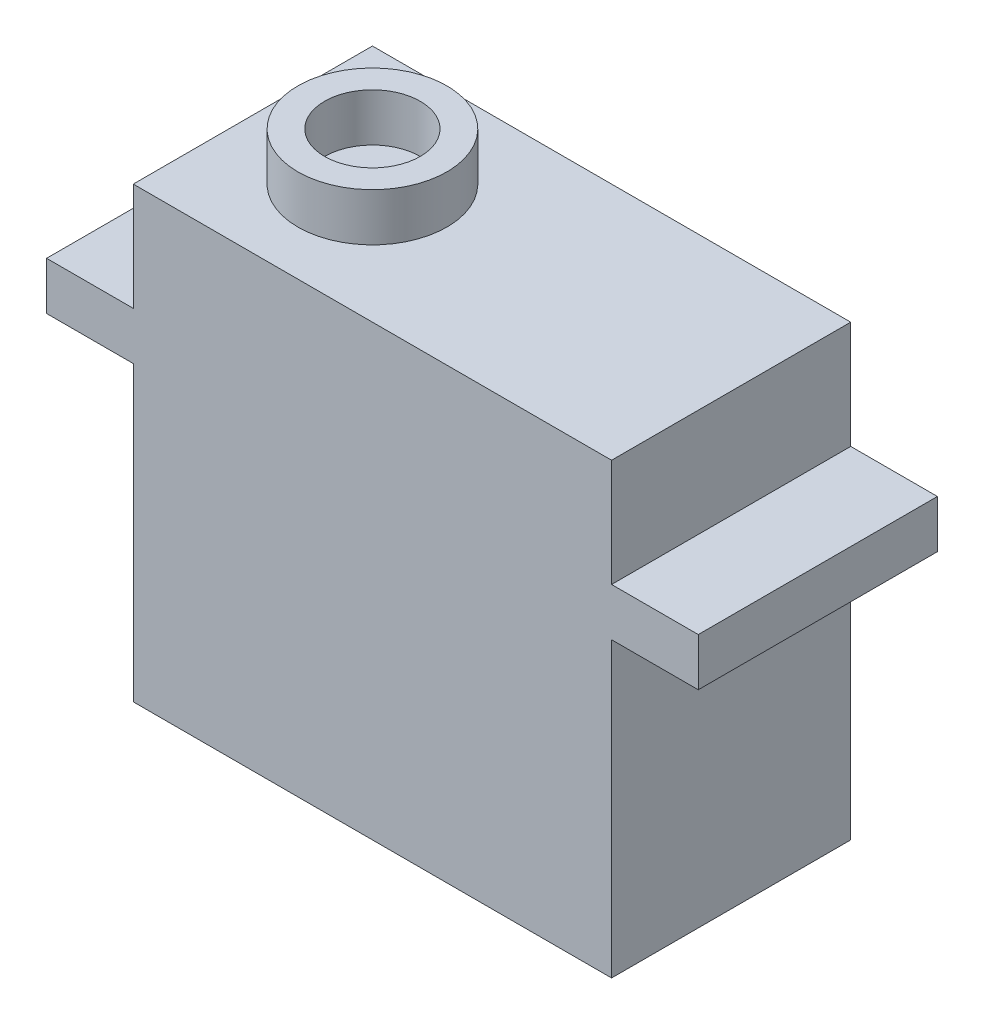
SolidWorks part; units mm, degrees
other "Markup2"
sketch "Sketch6"
other "DetailItem1"
ref_plane "Front Plane" through (0, 0, 0) normal (0, 0, 1) x (1, 0, 0)
ref_plane "Top Plane" through (0, 0, 0) normal (0, 1, 0) x (1, 0, 0)
ref_plane "Right Plane" through (0, 0, 0) normal (1, 0, 0) x (0, 0, -1)
sketch "Sketch1" plane through (0, 0, 0) normal (0, 1, 0) x (1, 0, 0)
  line L1 (0, 0) -> (40, 0)
  line L2 (0, 0) -> (0, 20)
  line L3 (0, 20) -> (40, 20)
  line L4 (40, 0) -> (40, 20)
  dimension "D1" = 20
  dimension "D2" = 40
extrude "Boss-Extrude1" add sketch "Sketch1" along normal blind 24.5
sketch "Sketch2" plane through (0, 24.5, 0) normal (0, 1, 0) x (1, 0, 0)
  line L0 (0, 20) -> (0, 0) construction
  line L5 (47.25, 20) -> (-7.25, 20)
  line L6 (47.25, 20) -> (47.25, 0)
  line L7 (47.25, 0) -> (-7.25, 0)
  line L8 (-7.25, 20) -> (-7.25, 0)
  line L9 (40, 0) -> (40, 20) construction
  dimension "D1" = 7.25
  dimension "D2" = 7.25
  dimension "D3" = 20
extrude "Boss-Extrude2" add sketch "Sketch2" along normal blind 4
sketch "Sketch3" plane through (0, 0, 0) normal (0, 0, 1) x (1, 0, 0)
  line L1 (0, 0) -> (40, 0)
  line L2 (0, 0) -> (0, 37.5)
  line L3 (0, 37.5) -> (40, 37.5)
  line L4 (40, 0) -> (40, 37.5)
  dimension "D1" = 37.5
  dimension "D2" = 40
extrude "Boss-Extrude3" add sketch "Sketch3" against normal blind 20
sketch "Sketch8" plane through (0, 37.5, 0) normal (0, 1, 0) x (1, 0, 0)
  line L0 (40, 20) -> (0, 20) construction
  line L1 (0, 0) -> (0, 20) construction
  circle A0 centre (10, 10) radius 6.2325
  circle A1 centre (10, 10) radius 4
  dimension "D3" = 8
  dimension "D1" = 10
  dimension "D2" = 10
extrude "Boss-Extrude4" add sketch "Sketch8" along normal blind 4 contours A0 | A1
sketch "Sketch9" plane through (0, 37.5, 0) normal (0, 1, 0) x (1, 0, 0)
  line L0 (10, 10) -> (40, 10)
  line L1 (40, 20) -> (40, 0) construction
